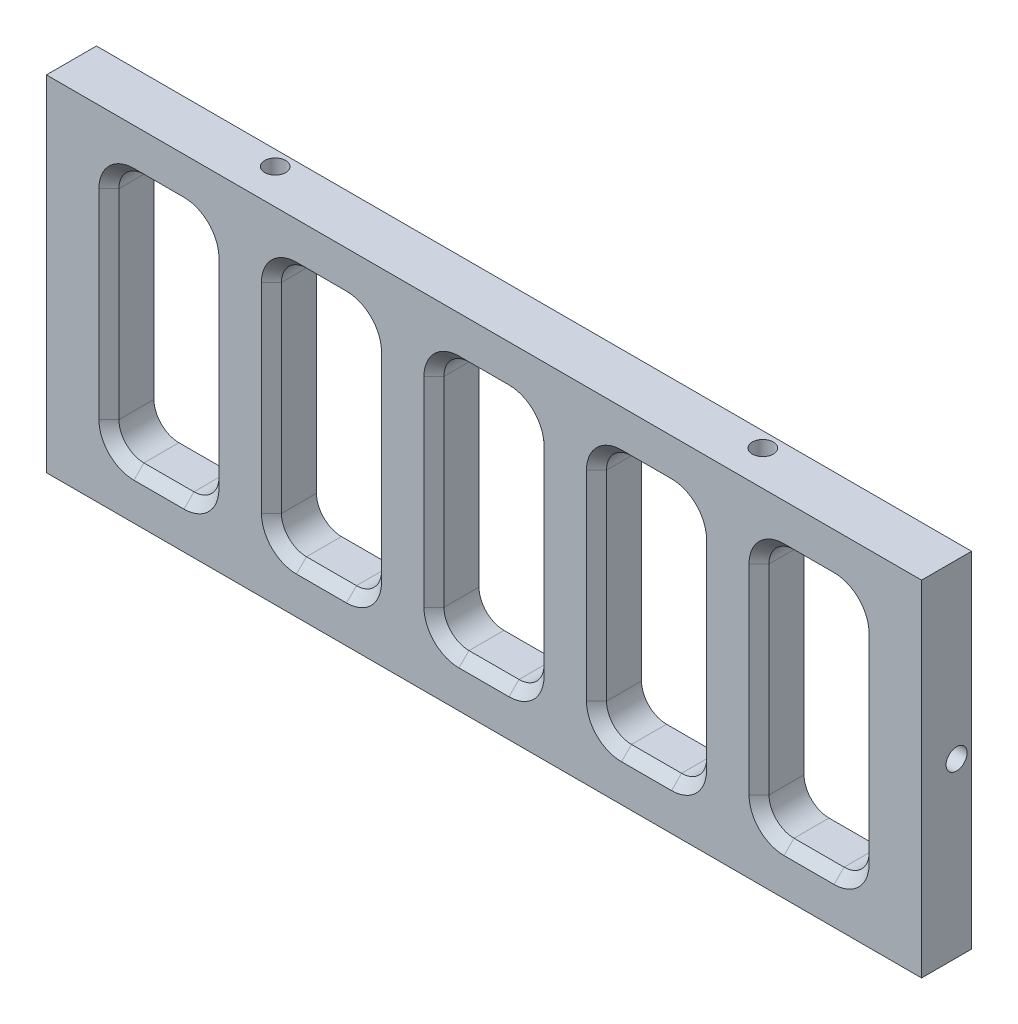
SolidWorks part; units mm, degrees
ref_plane "前视基准面" through (0, 0, 0) normal (0, 0, 1) x (1, 0, 0)
ref_plane "上视基准面" through (0, 0, 0) normal (0, 1, 0) x (1, 0, 0)
ref_plane "右视基准面" through (0, 0, 0) normal (1, 0, 0) x (0, 0, -1)
other "Configuration Table"
sketch "草图1" plane through (0, 0, 0) normal (1, 0, 0) x (0, 0, -1)
  line L1 (-5, -34.45) -> (5, -34.45)
  line L2 (-5, -34.45) -> (-5, 34.45)
  line L3 (-5, 34.45) -> (5, 34.45)
  line L4 (5, -34.45) -> (5, 34.45)
  line L5 (-5, -34.45) -> (5, 34.45) construction
  line L6 (-5, 34.45) -> (5, -34.45) construction
  point P0 (0, 0)
extrude "凸台-拉伸1" add sketch "草图1" along normal blind 175
sketch "草图2" plane through (0, 0, 5) normal (0, 0, 1) x (1, 0, 0)
  line L0 (175, 34.45) -> (0, -34.45)
  line L1 (0, 34.45) -> (175, -34.45)
  line L2 (77.5, -25) -> (77.5, 25) construction
  line L3 (82.5, -20) -> (92.5, -20) construction
  line L4 (0, 34.45) -> (0, -34.45)
  line L5 (0, -34.45) -> (175, -34.45)
  line L6 (175, -34.45) -> (175, 34.45)
  line L7 (175, 34.45) -> (0, 34.45)
  line L8 (0, 34.45) -> (0, -34.45)
  line L10 (175, -34.45) -> (175, 34.45)
  line L11 (175, 34.45) -> (0, 34.45)
  line L12 (82.5, -20) -> (82.5, 20) construction
  line L13 (82.5, 20) -> (92.5, 20) construction
  line L14 (92.5, -20) -> (92.5, 20) construction
  line L15 (82.5, -20) -> (92.5, 20) construction
  line L16 (82.5, 20) -> (92.5, -20) construction
  line L17 (77.5, 25) -> (97.5, 25) construction
  line L18 (97.5, -25) -> (97.5, 25) construction
  line L19 (77.5, -25) -> (97.5, -25) construction
  line L20 (82.5, -25) -> (92.5, -25)
  line L21 (82.5, 25) -> (92.5, 25)
  line L22 (97.5, 20) -> (97.5, -20)
  line L23 (77.5, -20) -> (77.5, 20)
  line L24 (110, -20) -> (110, 20)
  line L25 (115, 25) -> (125, 25)
  line L26 (130, 20) -> (130, -20)
  line L27 (115, -25) -> (125, -25)
  line L28 (142.5, -20) -> (142.5, 20)
  line L29 (147.5, 25) -> (157.5, 25)
  line L30 (162.5, 20) -> (162.5, -20)
  line L31 (147.5, -25) -> (157.5, -25)
  line L32 (45, -20) -> (45, 20)
  line L33 (50, 25) -> (60, 25)
  line L34 (65, 20) -> (65, -20)
  line L35 (50, -25) -> (60, -25)
  line L36 (12.5, -20) -> (12.5, 20)
  line L37 (17.5, 25) -> (27.5, 25)
  line L38 (32.5, 20) -> (32.5, -20)
  line L39 (17.5, -25) -> (27.5, -25)
  line L44 (0, -34.45) -> (175, -34.45)
  arc A0 (77.5, 20) -> (82.5, 25) centre (82.5, 20) cw
  arc A1 (92.5, 25) -> (97.5, 20) centre (92.5, 20) cw
  arc A2 (97.5, -20) -> (92.5, -25) centre (92.5, -20) cw
  arc A3 (82.5, -25) -> (77.5, -20) centre (82.5, -20) cw
  arc A4 (110, 20) -> (115, 25) centre (115, 20) cw
  arc A5 (125, 25) -> (130, 20) centre (125, 20) cw
  arc A6 (130, -20) -> (125, -25) centre (125, -20) cw
  arc A7 (115, -25) -> (110, -20) centre (115, -20) cw
  arc A8 (142.5, 20) -> (147.5, 25) centre (147.5, 20) cw
  arc A9 (157.5, 25) -> (162.5, 20) centre (157.5, 20) cw
  arc A10 (162.5, -20) -> (157.5, -25) centre (157.5, -20) cw
  arc A11 (147.5, -25) -> (142.5, -20) centre (147.5, -20) cw
  arc A12 (45, 20) -> (50, 25) centre (50, 20) cw
  arc A13 (60, 25) -> (65, 20) centre (60, 20) cw
  arc A14 (65, -20) -> (60, -25) centre (60, -20) cw
  arc A15 (50, -25) -> (45, -20) centre (50, -20) cw
  arc A16 (12.5, 20) -> (17.5, 25) centre (17.5, 20) cw
  arc A17 (27.5, 25) -> (32.5, 20) centre (27.5, 20) cw
  arc A18 (32.5, -20) -> (27.5, -25) centre (27.5, -20) cw
  arc A19 (17.5, -25) -> (12.5, -20) centre (17.5, -20) cw
  point P2 (87.5, 0)
  dimension "D3" = 3
  dimension "D4" = 3
  dimension "D5" = 10
  dimension "D1" = 0
  dimension "D2" = 5
extrude "切除-拉伸1" cut sketch "草图2" against normal blind 10 contours L34 L1 L32 L0 | A13 L33 A12 L32 L1 L34 | A15 L35 A14 L34 L0 L32 | A18 L0 L39 | A19 L39 L0 A18 L38 A17 L1 L37 A16 L36 | A17 L37 L1 | A1 L21 A0 L23 L1 L0 L22 | L23 L0 L1 | A3 L20 A2 L22 L1 L0 L23 | L22 L0 L1 | L26 L0 L24 L1 | A7 L27 A6 L26 L1 L24 | A5 L25 A4 L24 L0 L26 | A11 L1 L31 A10 L30 A9 L29 L0 A8 L28 | A8 L0 L29 | A11 L31 L1
chamfer "倒角1" distance 2 angle 45 40 edges at (161.0355, -23.5355, 5) (152.5, -25, 5) (143.9645, -23.5355, 5) (142.5, 0, 5) (162.5, 0, 5) (161.0355, 23.5355, 5) (152.5, 25, 5) (143.9645, 23.5355, 5) (128.5355, 23.5355, 5) (120, 25, 5) (111.4645, 23.5355, 5) (130, 0, 5) (110, 0, 5) (111.4645, -23.5355, 5) (120, -25, 5) (128.5355, -23.5355, 5) (96.0355, -23.5355, 5) (87.5, -25, 5) (78.9645, -23.5355, 5) (77.5, 0, 5) (97.5, 0, 5) (96.0355, 23.5355, 5) (78.9645, 23.5355, 5) (87.5, 25, 5) (63.5355, 23.5355, 5) (55, 25, 5) (46.4645, 23.5355, 5) (65, 0, 5) (45, 0, 5) (46.4645, -23.5355, 5) (55, -25, 5) (63.5355, -23.5355, 5) (31.0355, -23.5355, 5) (22.5, -25, 5) (13.9645, -23.5355, 5) (12.5, 0, 5) (32.5, 0, 5) (31.0355, 23.5355, 5) (22.5, 25, 5) (13.9645, 23.5355, 5)
sketch "草图5" plane through (0, 34.45, 0) normal (0, 1, 0) x (1, 0, 0)
  line L1 (175, -5) -> (0, -5) construction
  line L10 (0, 5) -> (175, -5) construction
  line L11 (175, 5) -> (0, -5) construction
  circle A0 centre (38.75, 2) radius 2.1
  circle A1 centre (136.25, 2) radius 2.1
  point P20 (87.5, 0)
  dimension "D1" = 97.5
  dimension "D2" = 48.75
  dimension "D3" = 7
extrude "切除-拉伸4" cut sketch "草图5" against normal blind 6
sketch "草图8" plane through (0, -34.45, 0) normal (0, -1, 0) x (1, 0, 0)
  circle A0 centre (136.25, -2) radius 2.1 construction
  circle A1 centre (38.75, -2) radius 2.1 construction
  circle A2 centre (136.25, -2) radius 2.1
  circle A3 centre (38.75, -2) radius 2.1
extrude "切除-拉伸7" cut sketch "草图8" against normal blind 6
sketch "草图9" plane through (175, 0, 0) normal (1, 0, 0) x (0, 0, -1)
  line L0 (-5, 0) -> (5, 0) construction
  line L1 (-5, 34.45) -> (-5, -34.45) construction
  line L2 (5, -34.45) -> (5, 34.45) construction
  circle A0 centre (2, 0) radius 2.1
  dimension "D1" = 7
extrude "切除-拉伸8" cut sketch "草图9" against normal blind 6 contours L0 A0 | L0 A0
sketch "草图10" plane through (0, 0, 0) normal (-1, 0, 0) x (0, 0, 1)
  circle A0 centre (-2, 0) radius 2.1 construction
  circle A1 centre (-2, 0) radius 2.1
extrude "切除-拉伸10" cut sketch "草图10" against normal blind 6
sketch "草图11" plane through (0, 0, -5) normal (0, 0, -1) x (-1, 0, 0)
  line L0 (-157.5, 30) -> (-17.5, 30)
  line L1 (-7.5, 20) -> (-7.5, -20)
  line L2 (-17.5, -30) -> (-157.5, -30)
  line L3 (-167.5, -20) -> (-167.5, 20)
  arc A0 (-17.5, -25) -> (-12.5, -20) centre (-17.5, -20) ccw construction
  arc A1 (-12.5, 20) -> (-17.5, 25) centre (-17.5, 20) ccw construction
  arc A2 (-162.5, -20) -> (-157.5, -25) centre (-157.5, -20) ccw construction
  arc A3 (-157.5, 25) -> (-162.5, 20) centre (-157.5, 20) ccw construction
  arc A4 (-17.5, -25) -> (-12.5, -20) centre (-17.5, -20) ccw construction
  arc A5 (-12.5, 20) -> (-17.5, 25) centre (-17.5, 20) ccw construction
  arc A6 (-162.5, -20) -> (-157.5, -25) centre (-157.5, -20) ccw construction
  arc A7 (-157.5, 25) -> (-162.5, 20) centre (-157.5, 20) ccw construction
  arc A8 (-17.5, -30) -> (-7.5, -20) centre (-17.5, -20) ccw
  arc A9 (-7.5, 20) -> (-17.5, 30) centre (-17.5, 20) ccw
  arc A10 (-167.5, -20) -> (-157.5, -30) centre (-157.5, -20) ccw
  arc A11 (-157.5, 30) -> (-167.5, 20) centre (-157.5, 20) ccw
  dimension "D1" = 5
extrude "切除-拉伸11" cut sketch "草图11" against normal blind 1
fillet "圆角1" radius 0.5 8 edges at (164.5711, -27.0711, -5) (167.5, 0, -5) (164.5711, 27.0711, -5) (87.5, 30, -5) (10.4289, 27.0711, -5) (7.5, 0, -5) (10.4289, -27.0711, -5) (87.5, -30, -5)
